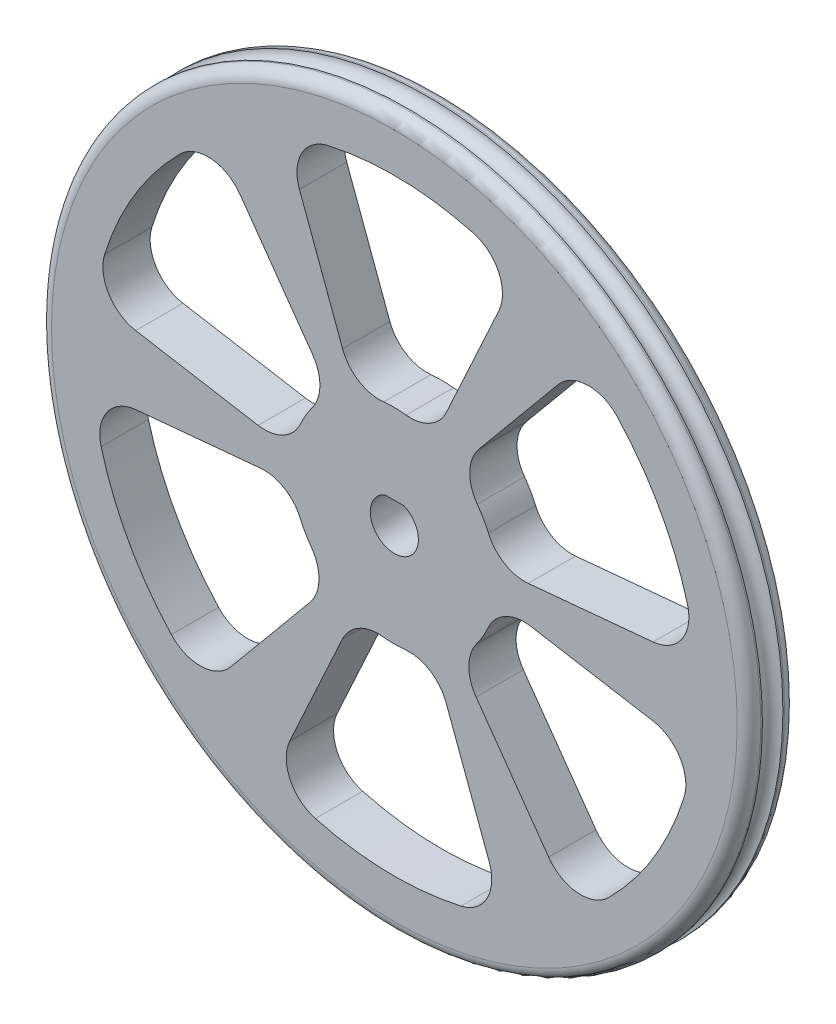
SolidWorks part; units mm, degrees
ref_plane "Plan de face" through (0, 0, 0) normal (0, 0, 1) x (1, 0, 0)
ref_plane "Plan de dessus" through (0, 0, 0) normal (0, 1, 0) x (1, 0, 0)
ref_plane "Plan de droite" through (0, 0, 0) normal (1, 0, 0) x (0, 0, -1)
sketch "Esquisse2" plane through (0, 0, 0) normal (1, 0, 0) x (0, 0, -1)
  line L0 (0, 128.7879) -> (0, -38.5432) construction
  line L1 (-77.2545, 0) -> (83.8756, 0) construction
  line L2 (3, 0) -> (-3, 0)
  line L4 (-3, 0) -> (-3, 43.5)
  line L5 (-1.5, 45) -> (-1.3, 45)
  line L6 (-1.3, 45) -> (-1.3, 48.0051) construction
  line L7 (-1.3, 48.0051) -> (0, 48.0051) construction
  line L8 (-1.3, 45) -> (1.3, 45) construction
  line L9 (1.3, 48.0051) -> (0, 48.0051) construction
  line L10 (1.3, 45) -> (1.3, 48.0051) construction
  line L11 (3, 0) -> (3, 43.5)
  line L12 (-3, 45) -> (3, 45) construction
  line L13 (77.2545, 0) -> (-83.8756, 0) construction
  line L15 (1.3, 45) -> (1.5, 45)
  arc A1 (-1.3, 45) -> (1.3, 45) centre (0, 45) ccw
  arc A2 (3, 43.5) -> (1.5, 45) centre (1.5, 43.5) ccw
  arc A3 (-3, 43.5) -> (-1.5, 45) centre (-1.5, 43.5) cw
  point P23 (0, 0)
  dimension "D2" = 1.5
  dimension "D1" = 45
  dimension "D3" = 1.3
  dimension "D6" = 3
revolve "Révolution1" add sketch "Esquisse2" angle 360 about L1
sketch "Esquisse3" plane through (0, 0, 0) normal (0, 0, 1) x (1, 0, 0)
  line L0 (0, 0) -> (22.2154, 0) construction
  line L1 (0, 0) -> (0, 9.136) construction
  line L2 (-1.2093, 2.8) -> (1.2093, 2.8)
  line L3 (-13.5007, -3.05) -> (10.4711, -3.05) construction
  arc A0 (-1.2093, 2.8) -> (1.2093, 2.8) centre (0, 0) ccw
  point P8 (0, 2.8)
  dimension "D1" = 3.05
  dimension "D2" = 2.8
  dimension "D3" = 5.85
extrude "Enlèv. mat.-Extru.3" cut sketch "Esquisse3" against normal through all both and the other way through all contours L2 A0
sketch "Esquisse4" plane through (0, 0, 0) normal (1, 0, 0) x (0, 0, -1)
  line L0 (0, 0) -> (46.0868, 0) construction
  arc A0 (-1.3, 45) -> (1.3, 45) centre (0, 45) ccw construction
  arc A1 (-1.3, 45) -> (1.3, 45) centre (0, 45) ccw
  circle A2 centre (0, 45) radius 1.3
  dimension "D2" = 2.6
  dimension "D1" = 45
revolve "Révolution2" [suppressed] add sketch "Esquisse4" angle 360 about L0
sketch "Esquisse5" plane through (0, 0, 3) normal (0, 0, 1) x (1, 0, 0)
  line L0 (-12.0456, 30.9445) -> (-6.5674, 16.164)
  line L1 (63.8365, 28.9354) -> (63.8365, 29.0818)
  line L2 (6.6185, 15.7936) -> (13.2609, 30.2596)
  line L3 (16.9869, 2.1651) -> (32.836, 3.6455)
  line L4 (20.7759, 25.904) -> (10.7147, 13.7695)
  line L5 (10.3684, -13.6286) -> (19.5751, -26.614)
  line L6 (32.8215, -5.0405) -> (17.2821, -2.3945)
  line L7 (-6.6185, -15.7936) -> (-13.2609, -30.2596)
  line L8 (12.0456, -30.9445) -> (6.5674, -16.164)
  line L9 (-16.9869, -2.1651) -> (-32.836, -3.6455)
  line L10 (-20.7759, -25.904) -> (-10.7147, -13.7695)
  line L11 (-10.3684, 13.6286) -> (-19.5751, 26.614)
  line L12 (-32.8215, 5.0405) -> (-17.2821, 2.3945)
  arc A0 (1.4983, 12.9134) -> (-1.3571, 12.929) centre (0, 0) ccw
  arc A1 (10.018, 37.1738) -> (-8.4553, 37.5601) centre (0, 0) ccw
  circle A2 centre (0, 0) radius 43.5 construction
  arc A3 (10.018, 37.1738) -> (13.2609, 30.2596) centre (8.717, 32.346) cw
  arc A4 (1.4983, 12.9134) -> (6.6185, 15.7936) centre (2.0746, 17.88) ccw
  arc A5 (-12.0456, 30.9445) -> (-8.4553, 37.5601) centre (-7.3572, 32.6821) cw
  arc A6 (-6.5674, 16.164) -> (-1.3571, 12.929) centre (-1.879, 17.9017) ccw
  arc A7 (11.9325, 5.1591) -> (16.9869, 2.1651) centre (16.5219, 7.1434) ccw
  arc A8 (37.2024, 9.911) -> (32.836, 3.6455) centre (32.371, 8.6239) cw
  arc A9 (37.2024, 9.911) -> (28.3003, 26.1025) centre (0, 0) ccw
  arc A10 (20.7759, 25.904) -> (28.3003, 26.1025) centre (24.6249, 22.7126) cw
  arc A11 (10.7147, 13.7695) -> (10.5183, 7.6398) centre (14.5638, 10.5781) ccw
  arc A12 (11.9325, 5.1591) -> (10.5183, 7.6398) centre (0, 0) ccw
  arc A13 (10.4342, -7.7543) -> (10.3684, -13.6286) centre (14.4473, -10.7367) ccw
  arc A14 (27.1844, -27.2628) -> (19.5751, -26.614) centre (23.654, -23.7221) cw
  arc A15 (27.1844, -27.2628) -> (36.7556, -11.4575) centre (0, 0) ccw
  arc A16 (32.8215, -5.0405) -> (36.7556, -11.4575) centre (31.9822, -9.9695) cw
  arc A17 (17.2821, -2.3945) -> (11.8754, -5.2892) centre (16.4428, -7.3235) ccw
  arc A18 (10.4342, -7.7543) -> (11.8754, -5.2892) centre (0, 0) ccw
  arc A19 (-1.4983, -12.9134) -> (-6.6185, -15.7936) centre (-2.0746, -17.88) ccw
  arc A20 (-10.018, -37.1738) -> (-13.2609, -30.2596) centre (-8.717, -32.346) cw
  arc A21 (-10.018, -37.1738) -> (8.4553, -37.5601) centre (0, 0) ccw
  arc A22 (12.0456, -30.9445) -> (8.4553, -37.5601) centre (7.3572, -32.6821) cw
  arc A23 (6.5674, -16.164) -> (1.3571, -12.929) centre (1.879, -17.9017) ccw
  arc A24 (-1.4983, -12.9134) -> (1.3571, -12.929) centre (0, 0) ccw
  arc A25 (-11.9325, -5.1591) -> (-16.9869, -2.1651) centre (-16.5219, -7.1434) ccw
  arc A26 (-37.2024, -9.911) -> (-32.836, -3.6455) centre (-32.371, -8.6239) cw
  arc A27 (-37.2024, -9.911) -> (-28.3003, -26.1025) centre (0, 0) ccw
  arc A28 (-20.7759, -25.904) -> (-28.3003, -26.1025) centre (-24.6249, -22.7126) cw
  arc A29 (-10.7147, -13.7695) -> (-10.5183, -7.6398) centre (-14.5638, -10.5781) ccw
  arc A30 (-11.9325, -5.1591) -> (-10.5183, -7.6398) centre (0, 0) ccw
  arc A31 (-10.4342, 7.7543) -> (-10.3684, 13.6286) centre (-14.4473, 10.7367) ccw
  arc A32 (-27.1844, 27.2628) -> (-19.5751, 26.614) centre (-23.654, 23.7221) cw
  arc A33 (-27.1844, 27.2628) -> (-36.7556, 11.4575) centre (0, 0) ccw
  arc A34 (-32.8215, 5.0405) -> (-36.7556, 11.4575) centre (-31.9822, 9.9695) cw
  arc A35 (-17.2821, 2.3945) -> (-11.8754, 5.2892) centre (-16.4428, 7.3235) ccw
  arc A36 (-10.4342, 7.7543) -> (-11.8754, 5.2892) centre (0, 0) ccw
  point P12 (15.5405, 35.2242)
  point P15 (4.8961, 12.0427)
  point P18 (-13.8855, 35.9088)
  point P21 (-5.0208, 11.9913)
  point P85 (0, 0)
  dimension "D1" = 6
  dimension "D4" = 5
  dimension "D5" = 5
  dimension "D2" = 13
  dimension "D3" = 45
extrude "Enlèv. mat.-Extru.8" cut sketch "Esquisse5" against normal through all both contours A36 A31 L11 A32 A33 A34 L12 A35 | A30 A25 L9 A26 A27 A28 L10 A29 | A24 A19 L7 A20 A21 A22 L8 A23 | A18 A13 L5 A14 A15 A16 L6 A17 | A12 A7 L3 A8 A9 A10 L4 A11 | L0 A6 A0 A4 L2 A3 A1 A5
